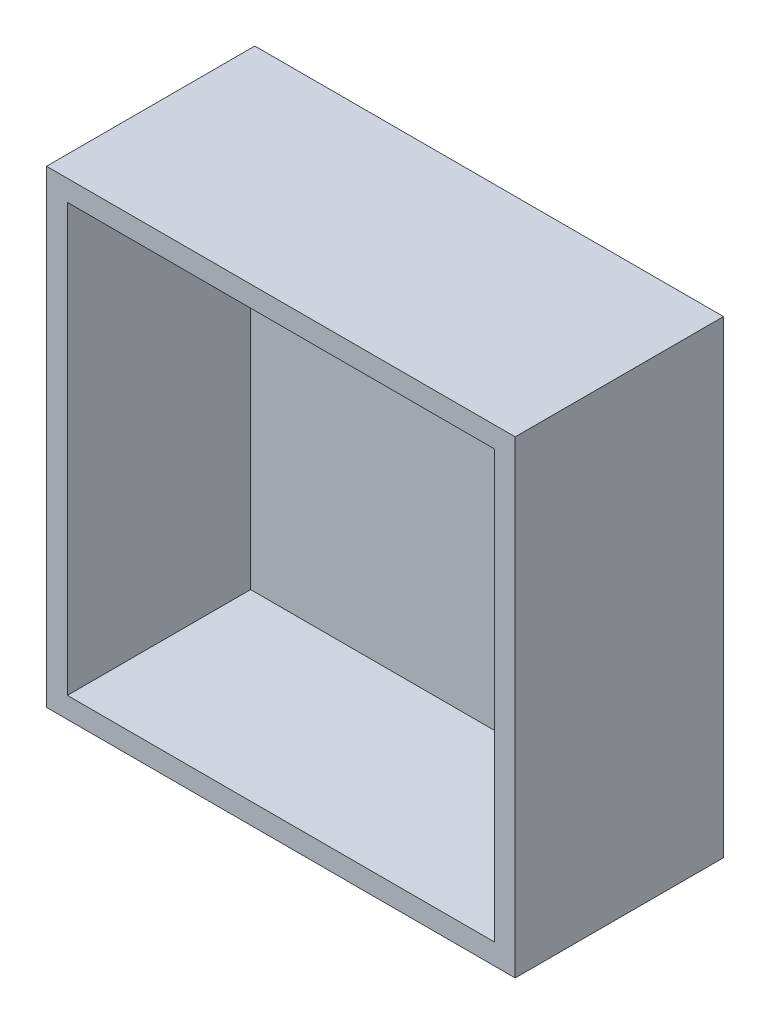
SolidWorks part; units mm, degrees
ref_plane "Спереди" through (0, 0, 0) normal (0, 0, 1) x (1, 0, 0)
ref_plane "Сверху" through (0, 0, 0) normal (0, 1, 0) x (1, 0, 0)
ref_plane "Справа" through (0, 0, 0) normal (1, 0, 0) x (0, 0, -1)
sketch "Эскиз1" plane through (0, 0, 0) normal (0, 0, 1) x (1, 0, 0)
  line L1 (-22.5, 22.5) -> (22.5, 22.5)
  line L2 (-22.5, 22.5) -> (-22.5, -22.5)
  line L3 (-22.5, -22.5) -> (22.5, -22.5)
  line L4 (22.5, 22.5) -> (22.5, -22.5)
  line L5 (-22.5, 22.5) -> (22.5, -22.5) construction
  line L6 (-22.5, -22.5) -> (22.5, 22.5) construction
  point P0 (0, 0)
  dimension "D1" = 45
  dimension "D2" = 45
extrude "Бобышка-Вытянуть1" add sketch "Эскиз1" along normal blind 20
sketch "Эскиз2" plane through (0, 0, 20) normal (0, 0, 1) x (1, 0, 0)
  line L0 (-20.5, 20.5) -> (-20.5, -20.5)
  line L1 (-22.5, 22.5) -> (22.5, 22.5) construction
  line L2 (-22.5, 22.5) -> (-22.5, -22.5) construction
  line L3 (-22.5, -22.5) -> (22.5, -22.5) construction
  line L4 (22.5, 22.5) -> (22.5, -22.5) construction
  line L5 (-22.5, 22.5) -> (22.5, -22.5) construction
  line L6 (-22.5, -22.5) -> (22.5, 22.5) construction
  line L7 (-20.5, -20.5) -> (20.5, -20.5)
  line L8 (20.5, 20.5) -> (20.5, -20.5)
  line L9 (-20.5, 20.5) -> (20.5, 20.5)
  point P0 (0, 0)
  dimension "D1" = 2
extrude "Вырез-Вытянуть1" cut sketch "Эскиз2" against normal blind 17 draft 2
